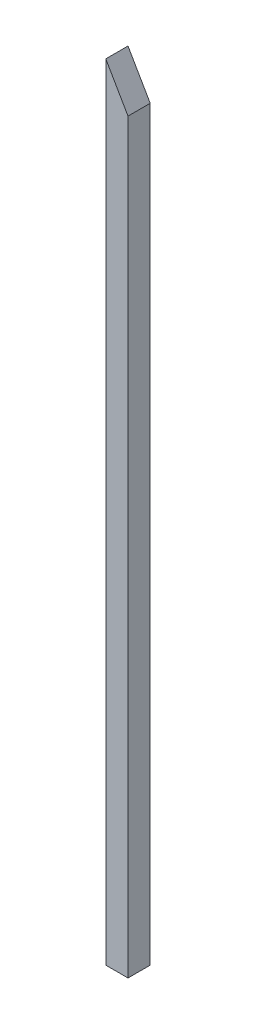
SolidWorks part; units mm, degrees
ref_plane "前视基准面" through (0, 0, 0) normal (0, 0, 1) x (1, 0, 0)
ref_plane "上视基准面" through (0, 0, 0) normal (0, 1, 0) x (1, 0, 0)
ref_plane "右视基准面" through (0, 0, 0) normal (1, 0, 0) x (0, 0, -1)
sketch "草图1" plane through (0, 0, 0) normal (0, 1, 0) x (1, 0, 0)
  line L1 (0, 0) -> (30, 0)
  line L2 (0, 0) -> (0, -30)
  line L3 (0, -30) -> (30, -30)
  line L4 (30, 0) -> (30, -30)
  dimension "D1" = 30
  dimension "D2" = 30
extrude "凸台-拉伸1" add sketch "草图1" along normal blind 600
sketch "草图2" plane through (0, 0, 30) normal (0, 0, 1) x (1, 0, 0)
  line L0 (0, 0) -> (30, 8.0385)
  line L1 (0, 0) -> (30, 0) construction
  line L2 (30, 600) -> (30, 0) construction
  line L3 (30, 8.0385) -> (30, 0)
  line L4 (30, 0) -> (0, 0)
  dimension "D1" = 15
extrude "切除-拉伸1" cut sketch "草图2" against normal up to next
sketch "草图3" plane through (0, 0, 0) normal (0, 0, -1) x (-1, 0, 0)
  line L0 (0, 600) -> (-30, 600)
  line L2 (0, 600) -> (-30, 488.0385)
  line L3 (-30, 600) -> (-30, 8.0385) construction
  line L4 (-30, 600) -> (-30, 488.0385)
extrude "切除-拉伸2" cut sketch "草图3" against normal up to next
sketch "草图4" plane through (0, 0, 30) normal (0, 0, 1) x (1, 0, 0)
  line L0 (0, 600) -> (0, -519.62)
  line L1 (0, 600) -> (0, 0) construction
  line L2 (0, -519.62) -> (30, -519.62)
  line L3 (30, -519.62) -> (30, 488.0385)
  line L4 (30, 488.0385) -> (0, 600)
  dimension "D1" = 1119.62
  dimension "D2" = 30
  dimension "D3" = 15
extrude "凸台-拉伸2" add sketch "草图4" against normal blind 30
sketch "草图5" plane through (0, 0, 30) normal (0, 0, 1) x (1, 0, 0)
  line L1 (0, 600) -> (0, -519.62) construction
  line L4 (0, 600) -> (0, 540)
  line L5 (30, 488.0385) -> (0, 600)
  line L6 (30, 488.0385) -> (0, 540)
extrude "切除-拉伸3" cut sketch "草图5" against normal up to surface (30 mm away) up to face at (15, 12.1996, 0)
